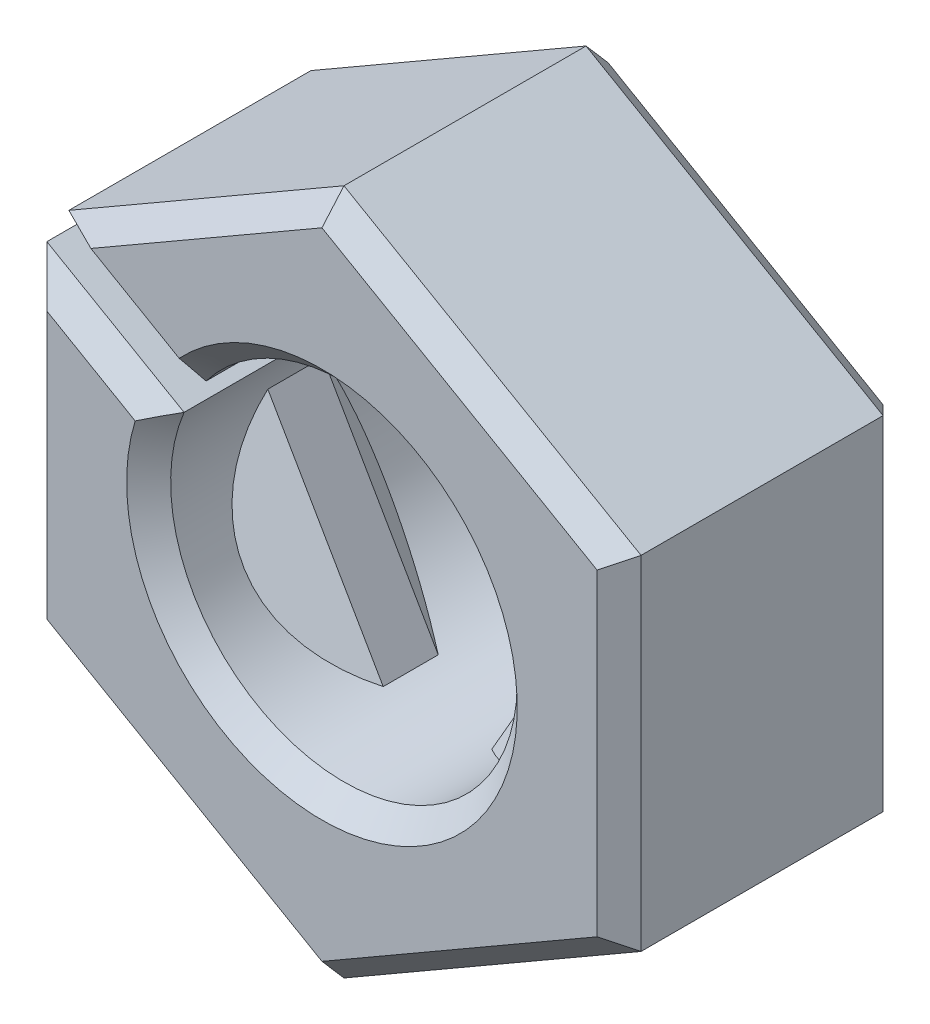
SolidWorks part; units mm, degrees
ref_plane "Front" through (0, 0, 0) normal (0, 0, 1) x (1, 0, 0)
ref_plane "Top" through (0, 0, 0) normal (0, 1, 0) x (1, 0, 0)
ref_plane "Right" through (0, 0, 0) normal (1, 0, 0) x (0, 0, -1)
sketch "Sketch1" plane through (0, 0, 0) normal (0, 0, 1) x (1, 0, 0)
  line L1 (2.7, -1.5588) -> (2.7, 1.5588)
  line L2 (2.7, 1.5588) -> (0, 3.1177)
  line L3 (0, 3.1177) -> (-2.7, 1.5588)
  line L4 (-2.7, 1.5588) -> (-2.7, -1.5588)
  line L5 (-2.7, -1.5588) -> (0, -3.1177)
  line L6 (0, -3.1177) -> (2.7, -1.5588)
  circle A0 centre (0, 0) radius 2.7 construction
  circle A1 centre (0, 0) radius 1.575
  dimension "D1" = 3.15
  dimension "D2" = 5.4
extrude "Boss-Extrude1" add sketch "Sketch1" along normal mid plane 2.6
sketch "Sketch3" plane through (0, 0, 0) normal (1, 0, 0) x (0, 0, -1)
  line L0 (-0.65, 1.575) -> (0.65, 1.575)
  line L1 (1.3, 1.575) -> (-1.3, 1.575) construction
  line L4 (0, 0) -> (0, 1.175) construction
  line L5 (0.65, 1.575) -> (0.25, 1.175)
  line L6 (0.25, 1.175) -> (-0.25, 1.175)
  line L7 (-0.25, 1.175) -> (-0.65, 1.575)
  dimension "D1" = 0.4
  dimension "D2" = 90
  dimension "D3" = 0.5
extrude "Clip" add sketch "Sketch3" along normal up to next and the other way up to next
pattern_circular "Clips x3" count 3 over 360 about axis through (0, 0, 0) along (0, 0, 1) of "Clip"
sketch "Sketch4" plane through (0, 0, 0) normal (0, 0, 1) x (1, 0, 0)
  line L0 (-2.7, 1.5588) -> (0, 0)
extrude "Split" cut sketch "Sketch4" against normal through all both and the other way through all thin thin type mid plane wall 0.4
chamfer "Deburs" distance 0.2 angle 45 18 edges at (1.364, -0.7875, -1.3) (2.7, 0, -1.3) (1.35, 2.3383, -1.3) (-1.25, 2.396, -1.3) (-2.7, -0.1155, -1.3) (-1.35, -2.3383, -1.3) (1.35, -2.3383, -1.3) (1.364, -0.7875, 1.3) (-1.35, -2.3383, 1.3) (-2.7, -0.1155, 1.3) (-1.25, 2.396, 1.3) (1.35, 2.3383, 1.3) (2.7, 0, 1.3) (1.35, -2.3383, 1.3) (-1.8765, 1.3143, -1.3) (-2.0765, 0.9679, -1.3) (-1.8765, 1.3143, 1.3) (-2.0765, 0.9679, 1.3)
equation "\"D1@Sketch1\"=\"Clearance Hole Diameter@Box Assy.Assembly\""
equation "\"D2@Sketch1\"=\"Nut Trap Diameter@Box Assy.Assembly\"-0.3mm"
equation "\"D1@Boss-Extrude1\"=\"Nut Trap Depth@Box Assy.Assembly\""
